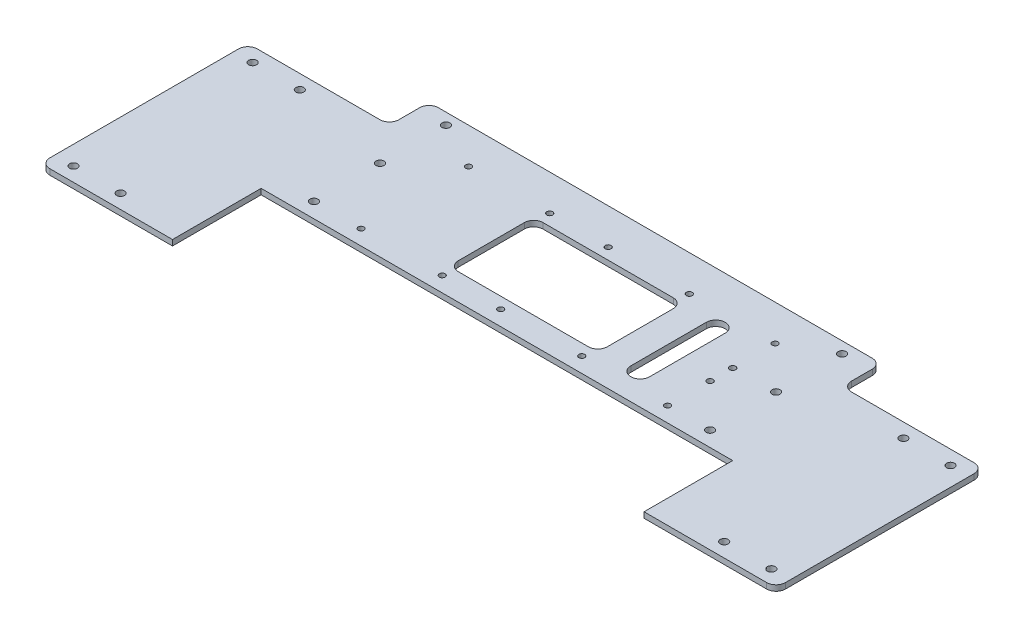
SolidWorks part; units mm, degrees
material "Thornel Mat VMA"
ref_plane "前视基准面" through (0, 0, 0) normal (0, 0, 1) x (1, 0, 0)
ref_plane "上视基准面" through (0, 0, 0) normal (0, 1, 0) x (1, 0, 0)
ref_plane "右视基准面" through (0, 0, 0) normal (1, 0, 0) x (0, 0, -1)
sketch "草图1" plane through (0, 0, 0) normal (0, 1, 0) x (1, 0, 0)
  line L0 (31.5759, -198.8718) -> (31.5759, 46.1282) construction
  line L1 (151.5759, -32.8718) -> (-88.4241, -32.8718)
  line L7 (-88.4241, -198.8718) -> (151.5759, -198.8718)
  line L8 (-88.4241, -198.8718) -> (-88.4241, -32.8718)
  line L10 (151.5759, -198.8718) -> (151.5759, -32.8718)
  line L16 (6.5759, -59.8718) -> (56.5759, -59.8718) construction
  line L18 (6.5759, -34.8718) -> (6.5759, -84.8718) construction
  line L19 (6.5759, -84.8718) -> (56.5759, -84.8718) construction
  line L20 (56.5759, -34.8718) -> (56.5759, -84.8718) construction
  line L21 (151.5759, -94.8718) -> (-88.4241, -94.8718) construction
  line L22 (-88.4241, -49.8718) -> (151.5759, -49.8718) construction
  circle A5 centre (6.5759, -84.8718) radius 1.6 construction
  circle A6 centre (56.5759, -84.8718) radius 1.6 construction
  point P6 (0, -121.2547)
  dimension "D2" = 166
  dimension "D4" = 240
  dimension "D9" = 10
  dimension "D12" = 50
  dimension "D15" = 45
extrude "构型与裁判孔" add sketch "草图1" along normal blind 3 contours L10 L21 L8 L7
sketch "草图4" plane through (0, 3, 0) normal (0, 1, 0) x (1, 0, 0)
  line L0 (-73.4241, -108.8718) -> (-73.4241, -198.8718) construction
  line L1 (77.0759, -32.8718) -> (77.0759, -198.8718) construction
  line L2 (151.5759, -32.8718) -> (-88.4241, -32.8718) construction
  line L3 (-88.4241, -198.8718) -> (-88.4241, -32.8718) construction
  line L4 (31.5759, -32.8718) -> (31.5759, -198.8718) construction
  line L5 (-88.4241, -198.8718) -> (151.5759, -198.8718) construction
  line L6 (-13.9241, -32.8718) -> (-13.9241, -198.8718) construction
  line L7 (-88.4241, -198.8718) -> (151.5759, -198.8718) construction
  line L8 (-88.4241, -198.8718) -> (151.5759, -198.8718) construction
  circle A0 centre (-73.4241, -73.8718) radius 2.1
  circle A1 centre (136.5759, -178.8718) radius 2.1
  circle A2 centre (-73.4241, -108.8718) radius 2.1
  circle A3 centre (-73.4241, -143.8718) radius 2.1
  circle A4 centre (-73.4241, -178.8718) radius 2.1
  circle A5 centre (136.5759, -143.8718) radius 2.1
  circle A6 centre (136.5759, -108.8718) radius 2.1
  circle A7 centre (136.5759, -73.8718) radius 2.1
  circle A8 centre (-73.4241, -38.8718) radius 2.1
  circle A9 centre (136.5759, -38.8718) radius 2.1
  circle A10 centre (77.0759, -188.8718) radius 1.55
  circle A11 centre (-13.9241, -188.8718) radius 1.55
  circle A12 centre (77.0759, -153.8718) radius 1.55
  circle A13 centre (-13.9241, -153.8718) radius 1.55
  dimension "D2" = 20
  dimension "D5" = 35
  dimension "D6" = 35
  dimension "D7" = 35
  dimension "D3" = 4.2
  dimension "D4" = 35
  dimension "D8" = 3.1
  dimension "D9" = 10
  dimension "D10" = 35
  dimension "D1" = 15
  dimension "D11" = 91
extrude "切除-拉伸3" cut sketch "草图4" against normal through all
sketch "草图5" plane through (0, 3, 0) normal (0, 1, 0) x (1, 0, 0)
  line L0 (71.0759, -57.8718) -> (-7.9241, -57.8718)
  line L1 (71.0759, -57.8718) -> (71.0759, -102.8718)
  line L2 (71.0759, -102.8718) -> (-7.9241, -102.8718)
  line L3 (-7.9241, -57.8718) -> (-7.9241, -102.8718)
  line L4 (71.0759, -57.8718) -> (-7.9241, -102.8718) construction
  line L5 (71.0759, -102.8718) -> (-7.9241, -57.8718) construction
  line L6 (31.5759, -32.8718) -> (31.5759, -104.1535) construction
  line L7 (71.0759, -80.3718) -> (-7.9241, -80.3718) construction
  line L8 (31.5759, -57.8718) -> (31.5759, -102.8718) construction
  line L9 (151.5759, -32.8718) -> (-88.4241, -32.8718) construction
  line L10 (91.0759, -100.3718) -> (91.0759, -60.3718) construction
  line L11 (86.0759, -100.3718) -> (86.0759, -60.3718)
  line L12 (96.0759, -100.3718) -> (96.0759, -60.3718)
  line L13 (31.5759, -102.8718) -> (31.5759, -198.8718) construction
  line L16 (-88.4241, -198.8718) -> (151.5759, -198.8718) construction
  line L17 (1.5759, -124.8718) -> (61.5759, -124.8718) construction
  line L18 (1.5759, -117.8718) -> (61.5759, -117.8718)
  line L19 (1.5759, -131.8718) -> (21.5759, -131.8718)
  line L20 (41.5759, -131.8718) -> (61.5759, -131.8718)
  line L21 (-73.4241, -143.8718) -> (136.5759, -143.8718) construction
  circle A0 centre (-5.4241, -51.8718) radius 1.55
  circle A1 centre (68.5759, -51.8718) radius 1.55
  circle A2 centre (68.5759, -108.8718) radius 1.55
  circle A3 centre (-5.4241, -108.8718) radius 1.55
  arc A4 (86.0759, -100.3718) -> (96.0759, -100.3718) centre (91.0759, -100.3718) ccw
  arc A5 (96.0759, -60.3718) -> (86.0759, -60.3718) centre (91.0759, -60.3718) ccw
  arc A8 (1.5759, -117.8718) -> (1.5759, -131.8718) centre (1.5759, -124.8718) ccw
  arc A9 (61.5759, -131.8718) -> (61.5759, -117.8718) centre (61.5759, -124.8718) ccw
  arc A10 (21.5759, -131.8718) -> (41.5759, -131.8718) centre (31.5759, -131.8718) ccw
  circle A11 centre (-45.4241, -143.8718) radius 10
  circle A12 centre (-73.4241, -143.8718) radius 2.1 construction
  circle A13 centre (108.5759, -143.8718) radius 10
  point P1 (110.5236, -62.9669)
  point P23 (91.0759, -80.3718)
  point P33 (31.5759, -124.8718)
  dimension "D3" = 3.1
  dimension "D7" = 5
  dimension "D10" = 7
  dimension "D13" = 20
  dimension "D14" = 28
  dimension "D1" = 79
  dimension "D2" = 45
  dimension "D4" = 37
  dimension "D5" = 28.5
  dimension "D6" = 25
  dimension "D8" = 40
  dimension "D9" = 15
  dimension "D11" = 60
  dimension "D12" = 15
extrude "切除-拉伸4" cut sketch "草图5" against normal through all
sketch "草图9" plane through (0, 0, 0) normal (0, -1, 0) x (1, 0, 0)
  line L0 (-1005.4241, 108.8718) -> (48994.5759, 108.8718) construction
  line L1 (-88.4241, 198.8718) -> (-88.4241, 32.8718) construction
  line L2 (-7.9241, 57.8718) -> (-7.9241, 102.8718) construction
  line L3 (-7.9241, 57.8718) -> (-7.9241, 102.8718) construction
  line L4 (-7.9241, 80.3718) -> (10.0801, 80.3718) construction
  line L5 (-1005.4241, 51.8718) -> (48994.5759, 51.8718) construction
  line L8 (91.0759, 105.3718) -> (91.0759, 78.9227) construction
  circle A0 centre (-5.4241, 108.8718) radius 1.55 construction
  circle A1 centre (-5.4241, 108.8718) radius 1.55 construction
  circle A2 centre (-73.4241, 108.8718) radius 2.1 construction
  circle A3 centre (-73.4241, 108.8718) radius 2.1 construction
  circle A4 centre (68.5759, 108.8718) radius 1.55 construction
  circle A5 centre (68.5759, 108.8718) radius 1.55
  circle A6 centre (-48.4241, 108.8718) radius 1.55
  circle A7 centre (25.5759, 108.8718) radius 1.55
  circle A8 centre (-5.4241, 51.8718) radius 1.55 construction
  circle A9 centre (25.5759, 51.8718) radius 1.55
  circle A10 centre (-48.4241, 51.8718) radius 1.55
  circle A12 centre (114.0759, 51.8718) radius 1.55
  circle A15 centre (68.5759, 51.8718) radius 1.55 construction
  circle A16 centre (114.0759, 74.3718) radius 1.6
  circle A17 centre (136.5759, 38.8718) radius 2.1 construction
  circle A18 centre (114.0759, 86.3718) radius 1.6
  circle A19 centre (114.0759, 108.8718) radius 1.55
  circle A20 centre (114.0759, 131.3718) radius 1.6
  arc A21 (96.0759, 100.3718) -> (86.0759, 100.3718) centre (91.0759, 100.3718) ccw construction
  circle A22 centre (68.0759, 131.3718) radius 1.6
  dimension "D3" = 3.1
  dimension "D5" = 3.1
  dimension "D7" = 3.2
  dimension "D8" = 3.1
  dimension "D9" = 45.5
  dimension "D10" = 22.5
  dimension "D1" = 15
  dimension "D2" = 74
  dimension "D4" = 25
  dimension "D6" = 74
  dimension "D11" = 22.5
sketch "草图6" plane through (0, 0, 0) normal (0, 1, 0) x (1, 0, 0)
  line L0 (-63.0381, -108.8718) -> (146.9619, -108.8718) construction
  line L1 (-88.4241, -53.8718) -> (-163.4241, -53.8718)
  line L2 (-88.4241, -198.8718) -> (-88.4241, -32.8718) construction
  line L3 (-163.4241, -53.8718) -> (-163.4241, -163.8718)
  line L4 (-73.4241, -108.8718) -> (136.5759, -108.8718) construction
  line L5 (-88.4241, -53.8718) -> (-88.4241, -163.8718)
  line L6 (-88.4241, -163.8718) -> (-163.4241, -163.8718)
  line L7 (31.5759, -32.8718) -> (31.5759, -198.8718) construction
  line L8 (151.5759, -32.8718) -> (-88.4241, -32.8718) construction
  line L9 (-88.4241, -198.8718) -> (151.5759, -198.8718) construction
  line L10 (151.5759, -53.8718) -> (151.5759, -163.8718)
  line L11 (151.5759, -163.8718) -> (226.5759, -163.8718)
  line L12 (226.5759, -53.8718) -> (226.5759, -163.8718)
  line L13 (151.5759, -53.8718) -> (226.5759, -53.8718)
  line L14 (-153.4241, -53.8718) -> (-153.4241, -163.8718) construction
  line L15 (-128.4241, -53.8718) -> (-128.4241, -163.8718) construction
  line L16 (-153.4241, -61.3718) -> (-128.4241, -61.3718) construction
  circle A0 centre (-153.4241, -61.3718) radius 2.1
  circle A1 centre (-153.4241, -156.3718) radius 2.1
  circle A2 centre (216.5759, -156.3718) radius 2.1
  circle A3 centre (216.5759, -61.3718) radius 2.1
  circle A4 centre (-128.4241, -61.3718) radius 2.1
  circle A5 centre (-128.4241, -156.3718) radius 2.1
  circle A6 centre (191.5759, -156.3718) radius 2.1
  circle A7 centre (191.5759, -61.3718) radius 2.1
  point P15 (-88.4241, -108.8718)
  point P16 (-163.4241, -108.8718)
  dimension "D4" = 95
  dimension "D6" = 4.2
  dimension "D7" = 4.2
  dimension "D1" = 75
  dimension "D2" = 55
  dimension "D3" = 10
  dimension "D5" = 25
extrude "凸台-拉伸1" add sketch "草图6" along normal blind 3
fillet "圆角1" radius 5 18 edges at (71.0759, 1.5, 102.8718) (-7.9241, 1.5, 102.8718) (-7.9241, 1.5, 57.8718) (71.0759, 1.5, 57.8718) (151.5759, 1.5, 32.8718) (-88.4241, 1.5, 32.8718) (151.5759, 1.5, 53.8718) (151.5759, 1.5, 163.8718) (-88.4241, 1.5, 163.8718) (-88.4241, 1.5, 53.8718) (226.5759, 1.5, 53.8718) (226.5759, 1.5, 163.8718) (151.5759, 1.5, 198.8718) (-88.4241, 1.5, 198.8718) (-163.4241, 1.5, 53.8718) (-163.4241, 1.5, 163.8718) (41.5759, 1.5, 131.8718) (21.5759, 1.5, 131.8718)
sketch "草图7" plane through (0, 3, 0) normal (0, 1, 0) x (1, 0, 0)
  line L0 (146.5759, -32.8718) -> (-83.4241, -32.8718) construction
  line L1 (-48.4241, -32.8718) -> (-48.4241, -82.8718)
  line L2 (-88.4241, -48.8718) -> (-88.4241, -37.8718) construction
  line L3 (-93.4241, -82.8718) -> (-48.4241, -82.8718)
  line L4 (-83.4241, -198.8718) -> (146.5759, -198.8718) construction
  line L5 (31.5759, -198.8718) -> (31.5759, 61.0332) construction
  line L6 (156.5759, -82.8718) -> (111.5759, -82.8718)
  line L7 (151.7733, -149.2908) -> (156.5759, -82.8718)
  line L8 (111.5759, -32.8718) -> (111.5759, -82.8718)
  line L10 (-48.4241, -32.8718) -> (111.5759, -32.8718)
  line L11 (-93.4241, -82.8718) -> (156.5759, -82.8718)
  line L12 (-93.4241, -82.8718) -> (-93.4241, -208.1915)
  line L13 (-93.4241, -208.1915) -> (156.5759, -208.1915)
  line L14 (156.5759, -82.8718) -> (156.5759, -208.1915)
  line L19 (-48.4241, -32.8718) -> (-48.4241, -82.8718)
  line L20 (-48.4241, -82.8718) -> (111.5759, -82.8718)
  line L21 (111.5759, -32.8718) -> (111.5759, -82.8718)
  dimension "D1" = 50
  dimension "D2" = 40
  dimension "D3" = 0
extrude "切除-拉伸5" [suppressed] cut sketch "草图7" against normal blind 10
fillet "圆角2" [suppressed] radius 10
fillet "圆角3" [suppressed] radius 10
sketch "草图8" plane through (0, 3, 0) normal (0, 1, 0) x (1, 0, 0)
  circle A0 centre (31.5759, -158.2052) radius 35.8 construction
  circle A1 centre (31.5759, -158.2052) radius 35.8 construction
  circle A2 centre (31.5759, -158.2052) radius 39
  dimension "D1" = 78
extrude "切除-拉伸6" cut sketch "草图8" against normal blind 10
extrude "切除-拉伸7" cut sketch "草图9" against normal blind 10
sketch "草图10" plane through (0, 0, 0) normal (0, -1, 0) x (1, 0, 0)
  line L0 (151.5759, 193.8718) -> (151.5759, 168.8718) construction
  line L1 (-93.4241, 198.8718) -> (156.5759, 198.8718)
  line L2 (-93.4241, 198.8718) -> (-93.4241, 116.8718)
  line L3 (-93.4241, 116.8718) -> (156.5759, 116.8718)
  line L4 (156.5759, 198.8718) -> (156.5759, 116.8718)
  line L5 (151.5759, 193.8718) -> (151.5759, 168.8718) construction
  line L6 (-163.4241, 58.8718) -> (-163.4241, 158.8718) construction
  line L7 (226.5759, 158.8718) -> (226.5759, 58.8718) construction
  line L8 (-83.4241, 198.8718) -> (146.5759, 198.8718) construction
  dimension "D1" = 82
  dimension "D2" = 70
  dimension "D3" = 70
  dimension "D4" = 0
extrude "切除-拉伸8" cut sketch "草图10" against normal blind 10
